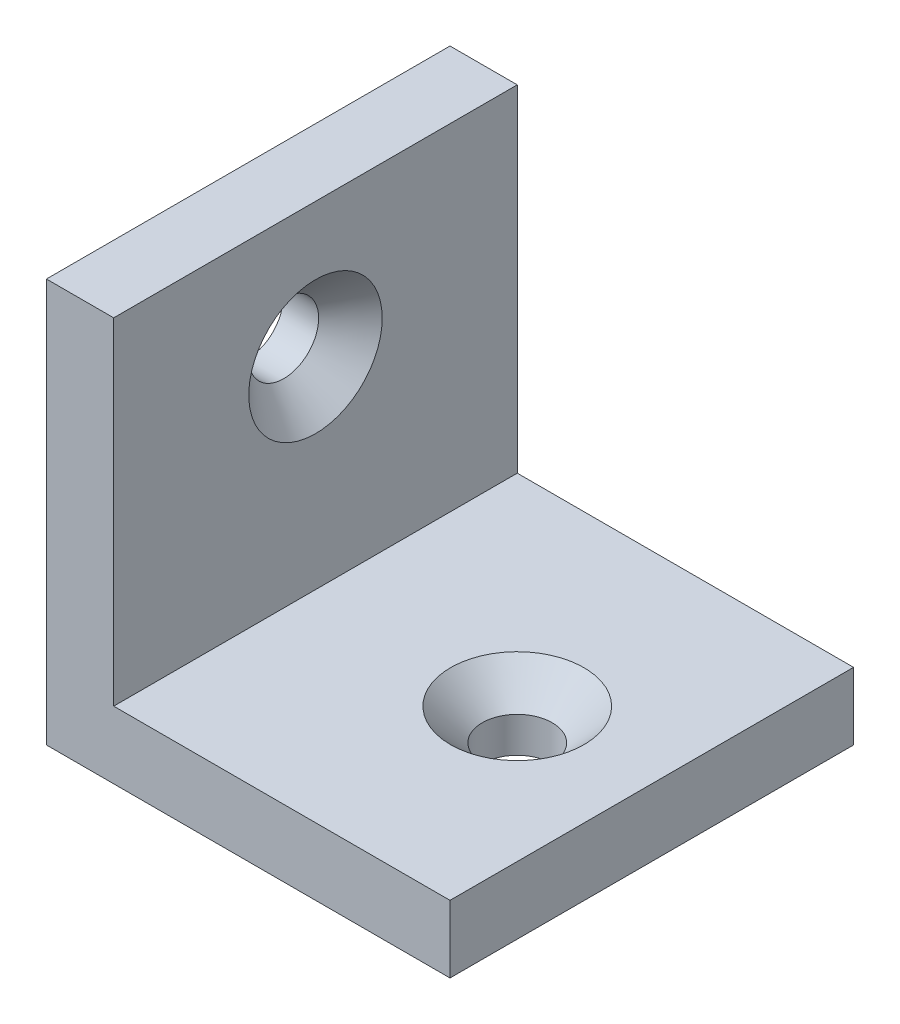
SolidWorks part; units mm, degrees
material "6061-T6 (SS)"
ref_plane "Front Plane" through (0, 0, 0) normal (0, 0, 1) x (1, 0, 0)
ref_plane "Top Plane" through (0, 0, 0) normal (0, 1, 0) x (1, 0, 0)
ref_plane "Right Plane" through (0, 0, 0) normal (1, 0, 0) x (0, 0, -1)
sketch "Sketch1" plane through (0, 0, 0) normal (0, 0, 1) x (1, 0, 0)
  line L1 (0, 0) -> (38.1, 0)
  line L2 (0, 0) -> (0, 4.5678)
  line L3 (6.35, 6.35) -> (38.1, 6.35)
  line L4 (38.1, 0) -> (38.1, 6.35)
  line L5 (0, 0) -> (4.5678, 0)
  line L6 (0, 0) -> (0, 38.1)
  line L7 (0, 38.1) -> (6.35, 38.1)
  line L8 (6.35, 6.35) -> (6.35, 38.1)
  dimension "D1" = 38.1
  dimension "D2" = 6.35
extrude "Boss-Extrude1" add sketch "Sketch1" along normal mid plane 38.1 contours L3 L8 L7 L6 L2 L1 L4
hole_wizard "CSK for M6 Flat Head Machine Screw1" positions "Sketch2" profile "Sketch3" countersink size "M6" standard "ANSI Metric" end condition through all
sketch "Sketch2" plane through (6.35, 0, 0) normal (1, 0, 0) x (0, 0, -1)
  line L0 (-19.05, 0) -> (19.05, 0) construction
  point P0 (0, 25.4)
  dimension "D1" = 25.4
sketch "Sketch3" plane through (6.35, 25.4, 0) normal (0, 1, 0) x (0, 0, -1)
  line L0 (0, 0) -> (0, 6.35)
  line L1 (0, 6.35) -> (3.3, 6.35)
  line L2 (3.3, 6.35) -> (3.3, 3)
  line L3 (3.3, 3) -> (6.3, 0)
  line L5 (6.3, 0) -> (0, 0)
  line L6 (-3.3, 3) -> (-6.3, 0) construction
  line L11 (0, -6.35) -> (0, 107.95) construction
  dimension "Thru Hole Dia." = 6.6
  dimension "Thru Hole Depth" = 6.35
  dimension "Near C'Sink Dia." = 12.6
  dimension "Near C'Sink Angle" = 90
hole_wizard "CSK for M6 Flat Head Machine Screw2" positions "Sketch4" profile "Sketch5" countersink size "M6" standard "ANSI Metric" end condition through all
sketch "Sketch4" plane through (0, 6.35, 0) normal (0, 1, 0) x (1, 0, 0)
  line L0 (0, -19.05) -> (0, 19.05) construction
  point P0 (25.4, 0)
  dimension "D1" = 25.4
sketch "Sketch5" plane through (25.4, 6.35, 0) normal (1, 0, 0) x (0, 0, 1)
  line L0 (0, 0) -> (0, 6.35)
  line L1 (0, 6.35) -> (3.3, 6.35)
  line L2 (3.3, 6.35) -> (3.3, 3)
  line L3 (3.3, 3) -> (6.3, 0)
  line L5 (6.3, 0) -> (0, 0)
  line L6 (-3.3, 3) -> (-6.3, 0) construction
  line L11 (0, -6.35) -> (0, 107.95) construction
  dimension "Thru Hole Dia." = 6.6
  dimension "Thru Hole Depth" = 6.35
  dimension "Near C'Sink Dia." = 12.6
  dimension "Near C'Sink Angle" = 90
